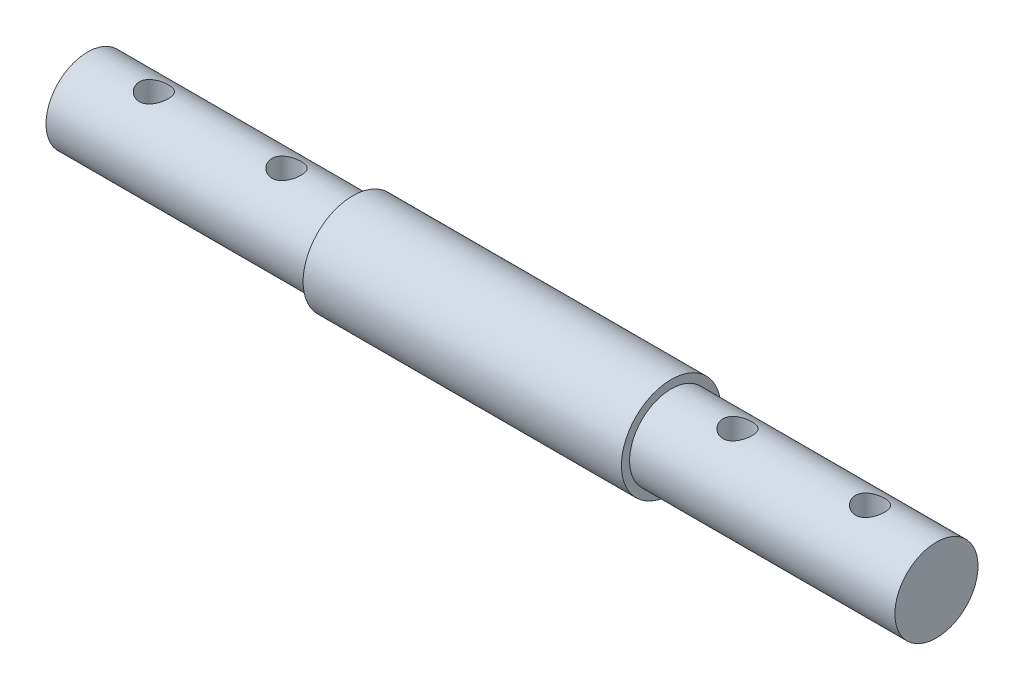
SolidWorks part; units mm, degrees
material "ASTM A36 Steel"
ref_plane "Front Plane" through (0, 0, 0) normal (0, 0, 1) x (1, 0, 0)
ref_plane "Top Plane" through (0, 0, 0) normal (0, 1, 0) x (1, 0, 0)
ref_plane "Right Plane" through (0, 0, 0) normal (1, 0, 0) x (0, 0, -1)
sketch "Sketch1" plane through (0, 0, 0) normal (1, 0, 0) x (0, 0, -1)
  circle A0 centre (0, 0) radius 37.5
  dimension "D1" = 75
extrude "Boss-Extrude1" add sketch "Sketch1" along normal blind 240
sketch "Sketch2" plane through (240, 0, 0) normal (1, 0, 0) x (0, 0, -1)
  circle A0 centre (0, 0) radius 31.34
  dimension "D1" = 62.68
extrude "Boss-Extrude2" add sketch "Sketch2" along normal blind 200
sketch "Sketch3" plane through (0, 0, 0) normal (-1, 0, 0) x (0, 0, 1)
  circle A0 centre (0, 0) radius 31.34
  dimension "D1" = 62.68
extrude "Boss-Extrude3" add sketch "Sketch3" along normal blind 200
sketch "Sketch4" plane through (0, 0, 0) normal (0, 1, 0) x (1, 0, 0)
  line L0 (0, 37.5) -> (0, -37.5) construction
  line L1 (240, -37.5) -> (240, 37.5) construction
  circle A0 centre (-50, 0) radius 11
  circle A1 centre (-150, 0) radius 11
  circle A2 centre (290, 0) radius 11
  circle A3 centre (390, 0) radius 11
  dimension "D1" = 22
  dimension "D2" = 22
  dimension "D3" = 50
  dimension "D4" = 100
  dimension "D5" = 22
  dimension "D6" = 22
  dimension "D7" = 50
  dimension "D8" = 100
extrude "Cut-Extrude1" cut sketch "Sketch4" against normal through all both and the other way through all
